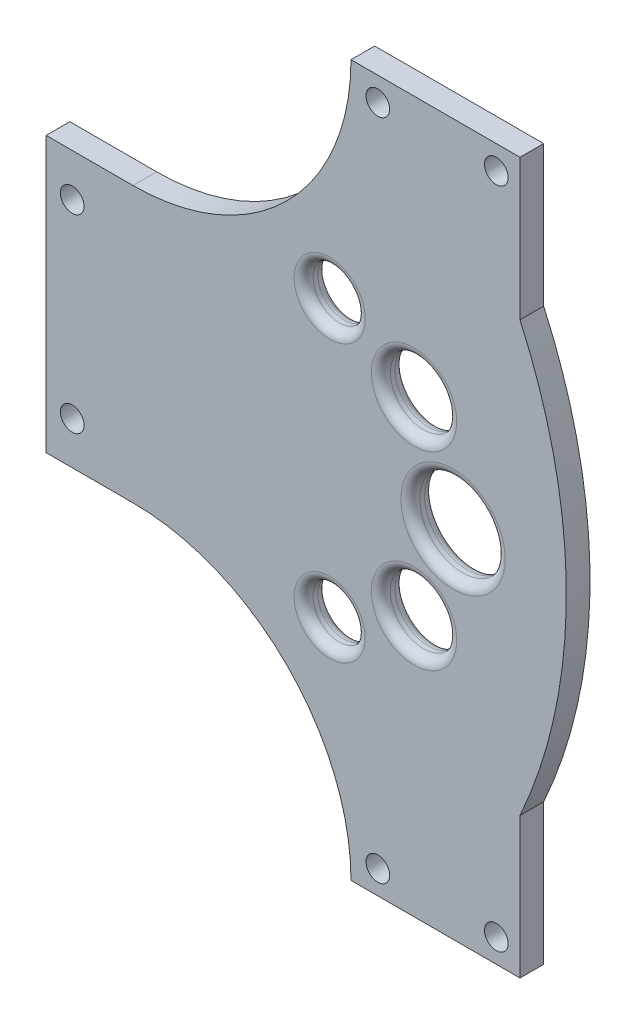
SolidWorks part; units mm, degrees
ref_plane "Спереди" through (0, 0, 0) normal (0, 0, 1) x (1, 0, 0)
ref_plane "Сверху" through (0, 0, 0) normal (0, 1, 0) x (1, 0, 0)
ref_plane "Справа" through (0, 0, 0) normal (1, 0, 0) x (0, 0, -1)
sketch "Эскиз1" plane through (0, 0, 0) normal (0, 0, 1) x (1, 0, 0)
  line L0 (0, 0) -> (0, 58)
  line L1 (0, 58) -> (18.3345, 58)
  line L2 (0, 29) -> (117.8644, 29) construction
  line L3 (64.3345, 104) -> (100, 104)
  line L4 (100, 104) -> (100, 74.2881)
  line L5 (100, -46) -> (100, -16.2881)
  line L6 (64.3345, -46) -> (100, -46)
  line L7 (0, 0) -> (18.3345, 0)
  arc A0 (64.3345, 104) -> (18.3345, 58) centre (18.3345, 104) cw
  arc A1 (64.3345, -46) -> (18.3345, 0) centre (18.3345, -46) ccw
  arc A2 (100, 74.2881) -> (100, -16.2881) centre (0, 29) cw
  dimension "D1" = 90
  dimension "D2" = 90
  dimension "D3" = 29
  dimension "D4" = 150
  dimension "D5" = 100
  dimension "D6" = 48.73
  dimension "D7" = 18.3345
extrude "Бобышка-Вытянуть2" add sketch "Эскиз1" along normal blind 5
sketch "Эскиз3" plane through (0, 0, 0) normal (0, 0, 1) x (1, 0, 0)
  line L0 (0, 29) -> (145.1475, 29) construction
  line L1 (0, 58) -> (0, 0) construction
  line L2 (43, 29) -> (59.8401, 58.1679) construction
  line L3 (43, 29) -> (77.641, 49) construction
  line L4 (43, 29) -> (77.641, 9) construction
  line L5 (43, 29) -> (59.8401, -0.1679) construction
  circle A0 centre (59.8401, 58.1679) radius 5.5
  circle A1 centre (77.641, 49) radius 7
  circle A2 centre (85.8761, 29) radius 9
  circle A3 centre (59.8401, -0.1679) radius 5.5
  circle A4 centre (77.641, 9) radius 7
  dimension "D1" = 30
  dimension "D4" = 11
  dimension "D5" = 14
  dimension "D9" = 18
  dimension "D2" = 30
  dimension "D3" = 43
  dimension "D6" = 29.1679
  dimension "D7" = 20
  dimension "D8" = 42.8761
extrude "Вырез-Вытянуть6" cut sketch "Эскиз3" along normal through all both and the other way through all
fillet "Скругление1" radius 2 10 edges at (65.3401, -0.1679, 0) (84.641, 9, 0) (94.8761, 29, 0) (84.641, 49, 0) (65.3401, 58.1679, 0) (54.3401, -0.1679, 5) (70.641, 9, 5) (94.8761, 29, 5) (84.641, 49, 5) (65.3401, 58.1679, 5)
sketch "Эскиз4" plane through (0, 0, 5) normal (0, 0, 1) x (1, 0, 0)
  line L1 (0, 29) -> (148.2324, 29) construction
  line L2 (0, 58) -> (0, 0) construction
  circle A0 centre (5.5, 49) radius 2.5
  circle A1 centre (5.5, 9) radius 2.5
  dimension "D1" = 5
  dimension "D2" = 5
  dimension "D3" = 20
  dimension "D4" = 20
  dimension "D5" = 5.5
  dimension "D6" = 5.5
extrude "Вырез-Вытянуть7" cut sketch "Эскиз4" against normal blind 10
sketch "Эскиз5" plane through (0, 0, 5) normal (0, 0, 1) x (1, 0, 0)
  line L0 (64.3345, -46) -> (100, -46) construction
  line L1 (100, -46) -> (100, -16.2881) construction
  line L2 (0, 29) -> (109.7771, 29) construction
  line L3 (0, 58) -> (0, 0) construction
  circle A0 centre (70, -41) radius 2.5
  circle A1 centre (95, -41) radius 2.5
  arc A2 (100, -16.2881) -> (100, 74.2881) centre (0, 29) ccw construction
  circle A3 centre (70, 99) radius 2.5
  circle A4 centre (95, 99) radius 2.5
  dimension "D1" = 5
  dimension "D2" = 5
  dimension "D3" = 5
  dimension "D4" = 5
  dimension "D5" = 5
  dimension "D6" = 25
  dimension "D7" = 70
  dimension "D8" = 95
extrude "Вырез-Вытянуть8" cut sketch "Эскиз5" against normal blind 10
sketch "Эскиз6" plane through (0, 0, 5) normal (0, 0, 1) x (1, 0, 0)
